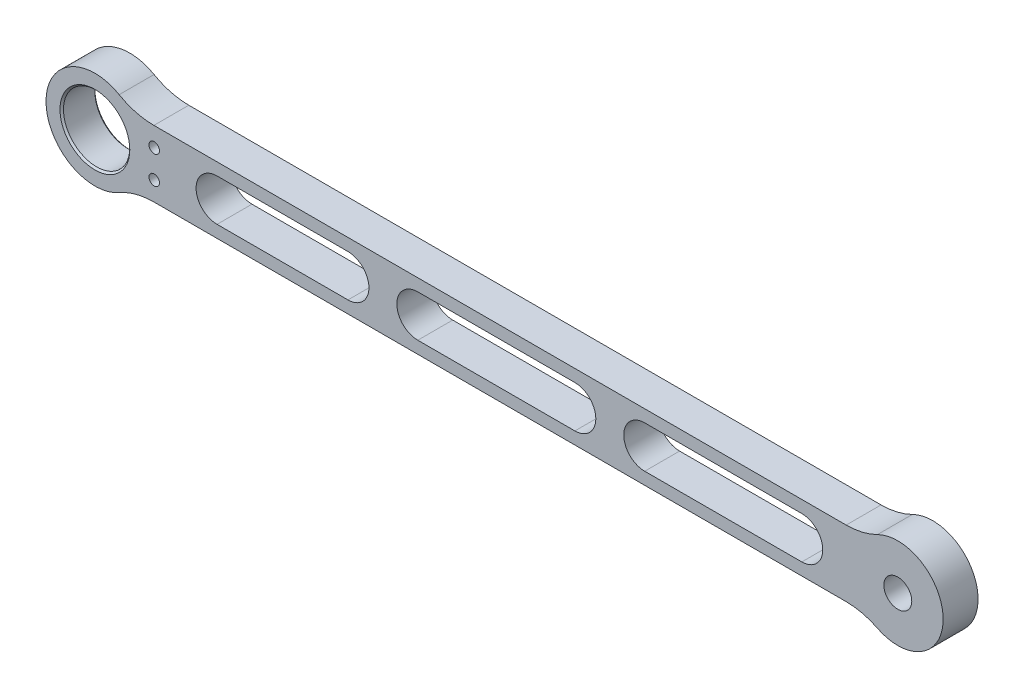
SolidWorks part; units mm, degrees
ref_plane "前视基准面" through (0, 0, 0) normal (0, 0, 1) x (1, 0, 0)
ref_plane "上视基准面" through (0, 0, 0) normal (0, 1, 0) x (1, 0, 0)
ref_plane "右视基准面" through (0, 0, 0) normal (1, 0, 0) x (0, 0, -1)
sketch "草图1" plane through (0, 0, 0) normal (0, 0, 1) x (1, 0, 0)
  line L0 (0, 0) -> (9.5, 0) construction
  line L1 (1.5589, 9.3712) -> (0, 9.5) construction
  line L2 (212.8026, -9.5) -> (16.9041, -9.5)
  line L4 (212.8026, 9.5) -> (16.9041, 9.5)
  line L6 (230, -9.5) -> (228.4411, -9.3712) construction
  line L7 (230, 9.5) -> (228.4411, 9.3712) construction
  line L8 (1.5589, -9.3712) -> (0, -9.5) construction
  line L9 (212.8026, 9.5) -> (215.2098, 9.5)
  line L10 (212.8026, -9.5) -> (215.2098, -9.5)
  line L11 (217, 0) -> (230, 0) construction
  circle A0 centre (0, 0) radius 9.5
  arc A1 (6.9605, 12.1471) -> (6.9605, -12.1471) centre (0, 0) ccw
  circle A2 centre (230, 0) radius 9.5
  arc A6 (6.9605, -12.1471) -> (16.9041, -9.5) centre (16.9041, -29.5) cw
  arc A7 (6.9605, 12.1471) -> (16.9041, 9.5) centre (16.9041, 29.5) ccw
  arc A8 (223.1064, -11.0217) -> (223.1064, 11.0217) centre (230, 0) ccw
  arc A11 (224.1736, -11.6212) -> (224.1736, 11.6212) centre (230, 0) ccw
  arc A12 (215.2098, -9.5) -> (224.1736, -11.6212) centre (215.2098, -29.5) cw
  arc A13 (224.1736, 11.6212) -> (215.2098, 9.5) centre (215.2098, 29.5) cw
  point P7 (115, 0)
  dimension "D1" = 20
  dimension "D2" = 9.5
  dimension "D4" = 230
  dimension "D3" = 9.5
extrude "凸台-拉伸1" add sketch "草图1" along normal blind 10
chamfer "倒角1" distance 0.5 angle 45 2 edges at (9.5, 0, 0) (9.5, 0, 10)
sketch "草图2" plane through (0, 0, 10) normal (0, 0, 1) x (1, 0, 0)
  line L0 (0, 0) -> (21.5, 0) construction
  line L1 (116.057, 0) -> (116.057, 9.5) construction
  line L2 (215.2098, 9.5) -> (16.9041, 9.5) construction
  line L3 (50, 0) -> (68, 0) construction
  line L4 (137.5, -6) -> (92.5, -6)
  line L6 (137.5, 6) -> (92.5, 6)
  line L8 (29, 0) -> (50, 0) construction
  line L9 (202.5, 0) -> (230, 0) construction
  line L10 (35, -6) -> (72.5, -6)
  line L12 (35, 6) -> (72.5, 6)
  line L14 (50, 0) -> (70.7692, 4.1538) construction
  line L15 (29.2308, 4.1538) -> (70.7692, -4.1538) construction
  line L16 (157.5, -6) -> (202.5, -6)
  line L18 (157.5, 6) -> (202.5, 6)
  line L22 (78.5, 0) -> (198, 0) construction
  arc A1 (72.5, -6) -> (72.5, 6) centre (72.5, 0) ccw
  arc A2 (92.5, 6) -> (92.5, -6) centre (92.5, 0) ccw
  arc A3 (137.5, -6) -> (137.5, 6) centre (137.5, 0) ccw
  arc A4 (157.5, 6) -> (157.5, -6) centre (157.5, 0) ccw
  arc A5 (202.5, -6) -> (202.5, 6) centre (202.5, 0) ccw
  arc A7 (35, 6) -> (35, -6) centre (35, 0) ccw
  point P12 (50, 0)
  point P17 (180, 0)
  dimension "D4" = 15
  dimension "D1" = 12
  dimension "D2" = 12
  dimension "D3" = 12
extrude "切除-拉伸2" cut sketch "草图2" against normal blind 10
sketch "草图3" plane through (0, 0, 10) normal (0, 0, 1) x (1, 0, 0)
  circle A0 centre (230, 0) radius 4
  circle A1 centre (230, 0) radius 9.5
extrude "凸台-拉伸2" add sketch "草图3" against normal blind 10
sketch "草图4" plane through (0, 0, 10) normal (0, 0, 1) x (1, 0, 0)
  circle A0 centre (230, 0) radius 6
extrude "切除-拉伸3" cut sketch "草图4" against normal blind 10
sketch "草图5" plane through (0, 0, 10) normal (0, 0, 1) x (1, 0, 0)
  circle A0 centre (230, 0) radius 6
  circle A1 centre (230, 0) radius 4
extrude "凸台-拉伸3" add sketch "草图5" against normal blind 10
sketch "草图6" plane through (0, 0, 10) normal (0, 0, 1) x (1, 0, 0)
  line L0 (0, 0) -> (17, 0) construction
  line L1 (17, 0) -> (17, 4) construction
  line L2 (17, 0) -> (17, -4) construction
  circle A0 centre (17, 4) radius 1.5
  circle A1 centre (17, -4) radius 1.5
extrude "切除-拉伸4" cut sketch "草图6" against normal through all
